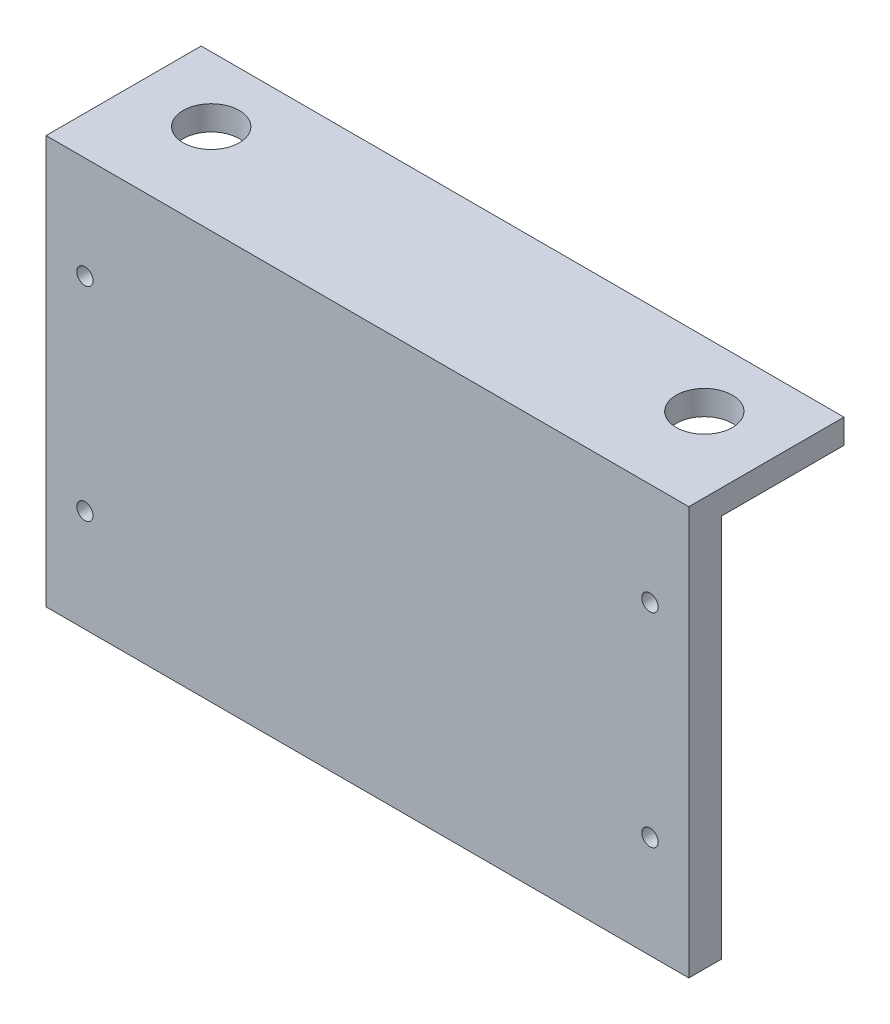
SolidWorks part; units mm, degrees
ref_plane "Front Plane" through (0, 0, 0) normal (0, 0, 1) x (1, 0, 0)
ref_plane "Top Plane" through (0, 0, 0) normal (0, 1, 0) x (1, 0, 0)
ref_plane "Right Plane" through (0, 0, 0) normal (1, 0, 0) x (0, 0, -1)
sketch "Sketch1" plane through (0, 0, 0) normal (0, 0, 1) x (1, 0, 0)
  line L1 (-50, 31.75) -> (50, 31.75)
  line L2 (-50, 31.75) -> (-50, -31.75)
  line L3 (-50, -31.75) -> (50, -31.75)
  line L4 (50, 31.75) -> (50, -31.75)
  line L5 (-50, 31.75) -> (50, -31.75) construction
  line L6 (-50, -31.75) -> (50, 31.75) construction
  point P0 (0, 0)
  dimension "D1" = 100
  dimension "D2" = 63.5
extrude "Boss-Extrude1" add sketch "Sketch1" along normal blind 5.08 contours L1 L4 L3 L2
sketch "Sketch3" plane through (0, 0, 0) normal (0, 0, -1) x (-1, 0, 0)
  line L0 (50, 31.75) -> (50, -31.75) construction
  line L1 (-50, 31.75) -> (50, 31.75)
  line L2 (-50, 31.75) -> (-50, 27.94)
  line L3 (-50, 27.94) -> (50, 27.94)
  line L4 (50, 31.75) -> (50, 27.94)
  dimension "D1" = 3.81
extrude "Boss-Extrude2" add sketch "Sketch3" along normal blind 19.05
sketch "Sketch8" plane through (0, 31.75, 0) normal (0, 1, 0) x (1, 0, 0)
  line L0 (0, 19.05) -> (0, -5.08)
  line L1 (-50, 19.05) -> (50, 19.05) construction
  line L2 (-50, -5.08) -> (50, -5.08) construction
  circle A0 centre (-38.3576, 8.9731) radius 4.3649
  circle A1 centre (38.3576, 8.9731) radius 4.3649
  point P8 (0, 0)
  point P9 (-38.3576, 8.9731)
extrude "Cut-Extrude2" cut sketch "Sketch8" against normal through all contours A0 | A1
sketch "Sketch10" plane through (0, 0, 5.08) normal (0, 0, 1) x (1, 0, 0)
  line L0 (-43.9547, -15.8267) -> (-43.9547, 15.8267)
  point P0 (-43.9547, 0)
  point P3 (-43.9547, 0)
sketch "Sketch11" plane through (0, 0, 5.08) normal (0, 0, 1) x (1, 0, 0)
  line L0 (43.9547, 0) -> (-43.9547, 0)
  line L1 (0, 0) -> (0, -31.75) construction
  line L2 (-50, -31.75) -> (50, -31.75) construction
  circle A0 centre (-43.9547, 15.8267) radius 1.27
  circle A1 centre (-43.9547, -15.8267) radius 1.27
  circle A2 centre (43.9547, -15.8267) radius 1.27
  circle A3 centre (43.9547, 15.8267) radius 1.27
  point P5 (0, 0)
extrude "Cut-Extrude5" cut sketch "Sketch11" against normal through all contours A2 | A1 | A0 | A3
